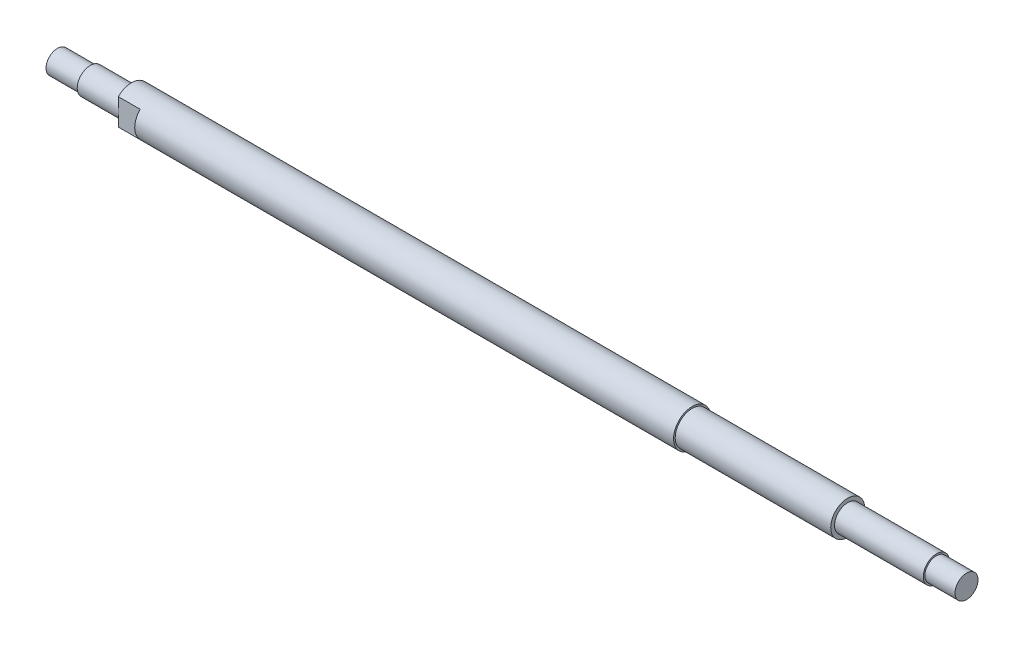
SolidWorks part; units mm, degrees
ref_plane "Front Plane" through (0, 0, 0) normal (0, 0, 1) x (1, 0, 0)
ref_plane "Top Plane" through (0, 0, 0) normal (0, 1, 0) x (1, 0, 0)
ref_plane "Right Plane" through (0, 0, 0) normal (1, 0, 0) x (0, 0, -1)
sketch "Sketch1" plane through (0, 0, 0) normal (0, 1, 0) x (1, 0, 0)
  line L0 (-12.2665, 0) -> (178.4892, 0) construction
  line L1 (0, 2.4) -> (0, 2.1)
  line L2 (0, 2.4) -> (7.5, 2.4)
  line L3 (7.5, 2.4) -> (7.5, 3.4)
  line L4 (7.5, 3.4) -> (109.9, 3.4)
  line L5 (109.9, 3.4) -> (109.9, 3.1)
  line L6 (109.9, 3.1) -> (138.3, 3.1)
  line L7 (138.3, 3.1) -> (138.3, 2.4)
  line L8 (138.3, 2.4) -> (154.5, 2.4)
  line L9 (154.5, 2.4) -> (154.5, 2.1)
  line L10 (154.5, 2.1) -> (160, 2.1)
  line L11 (160, 2.1) -> (160, 0)
  line L12 (0, 2.1) -> (-6, 2.1)
  line L13 (-6, 2.1) -> (-6, 0)
  line L14 (-6, 0) -> (160, 0)
  dimension "D1" = 166
  dimension "D2" = 4.8
  dimension "D3" = 102.4
  dimension "D4" = 6
  dimension "D5" = 7.5
  dimension "D6" = 28.4
  dimension "D7" = 16.2
  dimension "D8" = 6.8
  dimension "D9" = 6.2
  dimension "D10" = 4.2
revolve "Revolve1" add sketch "Sketch1" angle 360 about L0
cosmetic thread "Cosmetic Thread1" parameters "D2"=3.242
cosmetic thread "Cosmetic Thread2" parameters "D2"=3.242
cosmetic thread "Cosmetic Thread3" parameters "D1"=12, "D2"=4.917
sketch "Sketch2" plane through (0, 0, 0) normal (0, 1, 0) x (1, 0, 0)
  line L0 (7.5, 2.4) -> (11.5, 2.4)
  line L1 (11.5, 2.4) -> (11.5, 3.4)
  line L2 (109.9, 3.4) -> (7.5, 3.4) construction
  line L3 (4.6131, 0) -> (14.2833, 0) construction
  line L4 (11.5, -2.4) -> (11.5, -3.4)
  line L5 (7.5, -2.4) -> (11.5, -2.4)
  line L6 (11.5, 3.4) -> (7.5, 3.4)
  line L7 (7.5, 3.4) -> (7.5, 2.4)
  line L8 (7.5, -3.4) -> (7.5, -2.4)
  line L9 (11.5, -3.4) -> (7.5, -3.4)
  dimension "D1" = 4
extrude "Cut-Extrude1" cut sketch "Sketch2" against normal up to next and the other way up to next
